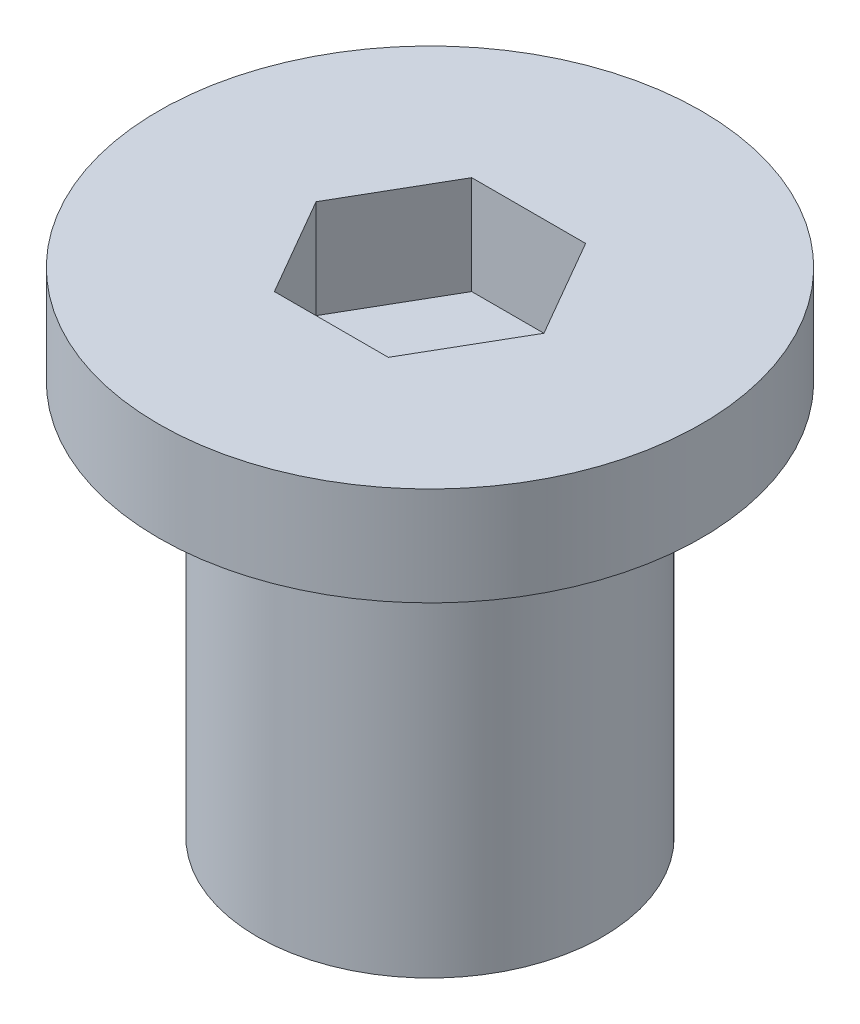
SolidWorks part; units mm, degrees
material "AISI 304"
ref_plane "Front Plane" through (0, 0, 0) normal (0, 0, 1) x (1, 0, 0)
ref_plane "Top Plane" through (0, 0, 0) normal (0, 1, 0) x (1, 0, 0)
ref_plane "Right Plane" through (0, 0, 0) normal (1, 0, 0) x (0, 0, -1)
sketch "Sketch1" plane through (0, 0, 0) normal (0, 1, 0) x (1, 0, 0)
  circle A0 centre (0, 0) radius 1.75
  dimension "D1" = 3.5
extrude "Boss-Extrude1" add sketch "Sketch1" along normal mid plane 4
sketch "Sketch2" plane through (0, 2, 0) normal (0, 1, 0) x (1, 0, 0)
  circle A0 centre (0, 0) radius 2.75
  dimension "D1" = 5.5
extrude "Boss-Extrude2" add sketch "Sketch2" along normal blind 1
sketch "Sketch3" plane through (0, 3, 0) normal (0, 1, 0) x (1, 0, 0)
  line L0 (1.1547, 0) -> (0.5774, 1)
  line L1 (0.5774, 1) -> (-0.5774, 1)
  line L2 (-0.5774, 1) -> (-1.1547, 0)
  line L3 (-1.1547, 0) -> (-0.5774, -1)
  line L4 (-0.5774, -1) -> (0.5774, -1)
  line L5 (0.5774, -1) -> (1.1547, 0)
  circle A0 centre (0, 0) radius 1 construction
  dimension "D1" = 1.1547
  dimension "D2" = 1.1547
  dimension "D3" = 1
  dimension "D4" = 1.1547
  dimension "D5" = 1.1547
  dimension "D6" = 1
extrude "Cut-Extrude1" cut sketch "Sketch3" against normal blind 1
